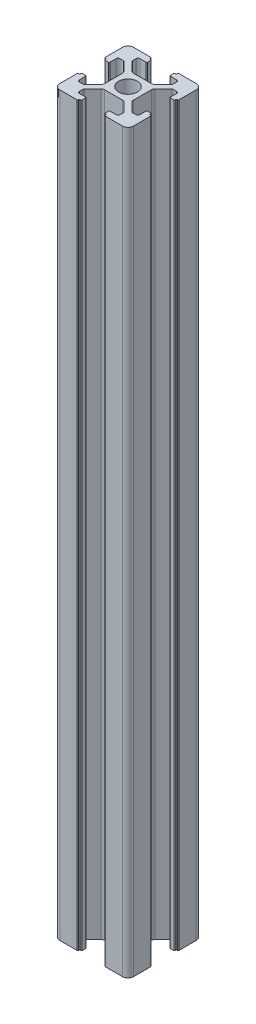
SolidWorks part; units mm, degrees
ref_plane "Front Plane" through (0, 0, 0) normal (0, 0, 1) x (1, 0, 0)
ref_plane "Top Plane" through (0, 0, 0) normal (0, 1, 0) x (1, 0, 0)
ref_plane "Right Plane" through (0, 0, 0) normal (1, 0, 0) x (0, 0, -1)
sketch "草图1" plane through (0, 0, 0) normal (0, 1, 0) x (1, 0, 0)
  line L5 (19.7612, 22.5335) -> (19.7612, 21.6335)
  line L8 (19.0112, 23.2335) -> (14.3612, 23.2335)
  line L9 (19.5612, 21.4335) -> (17.8612, 21.4335)
  line L10 (18.9612, 13.2335) -> (18.9612, 15.6586)
  line L11 (20.4361, 17.1335) -> (25.2863, 17.1335)
  line L12 (26.7612, 15.6586) -> (26.7612, 10.8084)
  line L13 (25.2863, 9.3335) -> (20.4361, 9.3335)
  line L14 (18.9612, 10.8084) -> (18.9612, 13.2335)
  line L15 (32.1612, 16.3335) -> (31.2612, 16.3335)
  line L16 (32.8612, 17.0835) -> (32.8612, 21.7335)
  line L17 (31.0612, 16.5335) -> (31.0612, 18.2335)
  line L18 (31.3612, 23.2335) -> (26.7112, 23.2335)
  line L19 (25.9612, 21.6335) -> (25.9612, 22.5335)
  line L20 (26.1612, 21.4335) -> (27.8612, 21.4335)
  line L21 (30.5612, 18.7335) -> (29.629, 18.7335)
  line L22 (32.6612, 16.8835) -> (32.5612, 16.8835)
  line L23 (28.3612, 20.0013) -> (28.3612, 20.9335)
  line L24 (27.0541, 16.3657) -> (29.2754, 18.5871)
  line L25 (25.9934, 17.4264) -> (28.2148, 19.6477)
  line L26 (32.3612, 16.6835) -> (32.3612, 16.5335)
  line L27 (26.5112, 23.0335) -> (26.5112, 22.9335)
  line L28 (12.8612, 21.7335) -> (12.8612, 17.0835)
  line L29 (26.3112, 22.7335) -> (26.1612, 22.7335)
  line L30 (14.4612, 16.3335) -> (13.5612, 16.3335)
  line L31 (25.9612, 3.9335) -> (25.9612, 4.8335)
  line L32 (26.7112, 3.2335) -> (31.3612, 3.2335)
  line L33 (14.6612, 16.5335) -> (14.6612, 18.2335)
  line L34 (17.3612, 20.9335) -> (17.3612, 20.0013)
  line L36 (19.2112, 23.0335) -> (19.2112, 22.9335)
  line L37 (16.0934, 18.7335) -> (15.1612, 18.7335)
  line L38 (19.729, 17.4264) -> (17.5077, 19.6477)
  line L39 (18.6683, 16.3657) -> (16.447, 18.5871)
  line L40 (19.4112, 22.7335) -> (19.5612, 22.7335)
  line L42 (13.0612, 16.8835) -> (13.1612, 16.8835)
  line L43 (13.3612, 16.6835) -> (13.3612, 16.5335)
  line L44 (26.1612, 5.0335) -> (27.8612, 5.0335)
  line L45 (32.8612, 4.7335) -> (32.8612, 9.3835)
  line L46 (31.2612, 10.1335) -> (32.1612, 10.1335)
  line L47 (31.0612, 9.9335) -> (31.0612, 8.2335)
  line L48 (28.3612, 5.5335) -> (28.3612, 6.4657)
  line L49 (26.5112, 3.4335) -> (26.5112, 3.5335)
  line L50 (29.629, 7.7335) -> (30.5612, 7.7335)
  line L51 (25.9934, 9.0406) -> (28.2148, 6.8193)
  line L52 (27.0541, 10.1013) -> (29.2754, 7.8799)
  line L53 (26.3112, 3.7335) -> (26.1612, 3.7335)
  line L54 (32.6612, 9.5835) -> (32.5612, 9.5835)
  line L55 (32.3612, 9.7835) -> (32.3612, 9.9335)
  line L56 (13.5612, 10.1335) -> (14.4612, 10.1335)
  line L57 (12.8612, 9.3835) -> (12.8612, 4.7335)
  line L58 (14.6612, 9.9335) -> (14.6612, 8.2335)
  line L59 (14.3612, 3.2335) -> (19.0112, 3.2335)
  line L60 (19.7612, 4.8335) -> (19.7612, 3.9335)
  line L61 (19.5612, 5.0335) -> (17.8612, 5.0335)
  line L62 (15.1612, 7.7335) -> (16.0934, 7.7335)
  line L63 (13.0612, 9.5835) -> (13.1612, 9.5835)
  line L64 (17.3612, 6.4657) -> (17.3612, 5.5335)
  line L65 (18.6683, 10.1013) -> (16.447, 7.8799)
  line L66 (19.729, 9.0406) -> (17.5077, 6.8193)
  line L67 (13.3612, 9.7835) -> (13.3612, 9.9335)
  line L68 (19.2112, 3.4335) -> (19.2112, 3.5335)
  line L69 (19.4112, 3.7335) -> (19.5612, 3.7335)
  circle A0 centre (22.8612, 13.2335) radius 2.55
  arc A1 (14.3612, 23.2335) -> (12.8612, 21.7335) centre (14.3612, 21.7335) ccw
  arc A2 (32.8612, 21.7335) -> (31.3612, 23.2335) centre (31.3612, 21.7335) ccw
  arc A3 (31.3612, 3.2335) -> (32.8612, 4.7335) centre (31.3612, 4.7335) ccw
  arc A4 (12.8612, 4.7335) -> (14.3612, 3.2335) centre (14.3612, 4.7335) ccw
  arc A5 (14.6612, 8.2335) -> (15.1612, 7.7335) centre (15.1612, 8.2335) ccw
  arc A6 (17.8612, 5.0335) -> (17.3612, 5.5335) centre (17.8612, 5.5335) cw
  arc A7 (27.8612, 5.0335) -> (28.3612, 5.5335) centre (27.8612, 5.5335) ccw
  arc A8 (31.0612, 8.2335) -> (30.5612, 7.7335) centre (30.5612, 8.2335) cw
  arc A9 (31.0612, 18.2335) -> (30.5612, 18.7335) centre (30.5612, 18.2335) ccw
  arc A10 (27.8612, 21.4335) -> (28.3612, 20.9335) centre (27.8612, 20.9335) cw
  arc A11 (17.8612, 21.4335) -> (17.3612, 20.9335) centre (17.8612, 20.9335) ccw
  arc A12 (14.6612, 18.2335) -> (15.1612, 18.7335) centre (15.1612, 18.2335) cw
  arc A13 (16.0934, 7.7335) -> (16.447, 7.8799) centre (16.0934, 8.2335) ccw
  arc A14 (17.3612, 6.4657) -> (17.5077, 6.8193) centre (17.8612, 6.4657) cw
  arc A15 (28.3612, 6.4657) -> (28.2148, 6.8193) centre (27.8612, 6.4657) ccw
  arc A16 (29.629, 7.7335) -> (29.2754, 7.8799) centre (29.629, 8.2335) cw
  arc A17 (29.629, 18.7335) -> (29.2754, 18.5871) centre (29.629, 18.2335) ccw
  arc A18 (28.3612, 20.0013) -> (28.2148, 19.6477) centre (27.8612, 20.0013) cw
  arc A19 (17.5077, 19.6477) -> (17.3612, 20.0013) centre (17.8612, 20.0013) cw
  arc A20 (16.447, 18.5871) -> (16.0934, 18.7335) centre (16.0934, 18.2335) ccw
  arc A21 (14.4612, 10.1335) -> (14.6612, 9.9335) centre (14.4612, 9.9335) cw
  arc A22 (13.5612, 10.1335) -> (13.3612, 9.9335) centre (13.5612, 9.9335) ccw
  arc A23 (13.1612, 9.5835) -> (13.3612, 9.7835) centre (13.1612, 9.7835) ccw
  arc A24 (12.8612, 9.3835) -> (13.0612, 9.5835) centre (13.0612, 9.3835) cw
  arc A25 (19.0112, 3.2335) -> (19.2112, 3.4335) centre (19.0112, 3.4335) ccw
  arc A26 (19.2112, 3.5335) -> (19.4112, 3.7335) centre (19.4112, 3.5335) cw
  arc A27 (19.7612, 3.9335) -> (19.5612, 3.7335) centre (19.5612, 3.9335) cw
  arc A28 (19.7612, 4.8335) -> (19.5612, 5.0335) centre (19.5612, 4.8335) ccw
  arc A29 (26.7112, 3.2335) -> (26.5112, 3.4335) centre (26.7112, 3.4335) cw
  arc A30 (26.5112, 3.5335) -> (26.3112, 3.7335) centre (26.3112, 3.5335) ccw
  arc A31 (25.9612, 3.9335) -> (26.1612, 3.7335) centre (26.1612, 3.9335) ccw
  arc A32 (25.9612, 4.8335) -> (26.1612, 5.0335) centre (26.1612, 4.8335) cw
  arc A33 (32.8612, 9.3835) -> (32.6612, 9.5835) centre (32.6612, 9.3835) ccw
  arc A34 (32.5612, 9.5835) -> (32.3612, 9.7835) centre (32.5612, 9.7835) cw
  arc A35 (32.1612, 10.1335) -> (32.3612, 9.9335) centre (32.1612, 9.9335) cw
  arc A36 (31.2612, 10.1335) -> (31.0612, 9.9335) centre (31.2612, 9.9335) ccw
  arc A37 (32.8612, 17.0835) -> (32.6612, 16.8835) centre (32.6612, 17.0835) cw
  arc A38 (32.5612, 16.8835) -> (32.3612, 16.6835) centre (32.5612, 16.6835) ccw
  arc A39 (32.1612, 16.3335) -> (32.3612, 16.5335) centre (32.1612, 16.5335) ccw
  arc A40 (31.2612, 16.3335) -> (31.0612, 16.5335) centre (31.2612, 16.5335) cw
  arc A41 (25.9612, 21.6335) -> (26.1612, 21.4335) centre (26.1612, 21.6335) ccw
  arc A42 (25.9612, 22.5335) -> (26.1612, 22.7335) centre (26.1612, 22.5335) cw
  arc A43 (26.5112, 22.9335) -> (26.3112, 22.7335) centre (26.3112, 22.9335) cw
  arc A44 (26.7112, 23.2335) -> (26.5112, 23.0335) centre (26.7112, 23.0335) ccw
  arc A45 (14.4612, 16.3335) -> (14.6612, 16.5335) centre (14.4612, 16.5335) ccw
  arc A46 (19.7612, 21.6335) -> (19.5612, 21.4335) centre (19.5612, 21.6335) cw
  arc A47 (19.5612, 22.7335) -> (19.7612, 22.5335) centre (19.5612, 22.5335) cw
  arc A48 (19.2112, 22.9335) -> (19.4112, 22.7335) centre (19.4112, 22.9335) ccw
  arc A49 (19.0112, 23.2335) -> (19.2112, 23.0335) centre (19.0112, 23.0335) cw
  arc A50 (13.3612, 16.5335) -> (13.5612, 16.3335) centre (13.5612, 16.5335) ccw
  arc A51 (13.1612, 16.8835) -> (13.3612, 16.6835) centre (13.1612, 16.6835) cw
  arc A52 (12.8612, 17.0835) -> (13.0612, 16.8835) centre (13.0612, 17.0835) ccw
  arc A53 (18.9612, 10.8084) -> (18.6683, 10.1013) centre (17.9612, 10.8084) cw
  arc A54 (19.729, 9.0406) -> (20.4361, 9.3335) centre (20.4361, 8.3335) cw
  arc A55 (25.9934, 9.0406) -> (25.2863, 9.3335) centre (25.2863, 8.3335) ccw
  arc A56 (27.0541, 10.1013) -> (26.7612, 10.8084) centre (27.7612, 10.8084) cw
  arc A57 (27.0541, 16.3657) -> (26.7612, 15.6586) centre (27.7612, 15.6586) ccw
  arc A58 (25.9934, 17.4264) -> (25.2863, 17.1335) centre (25.2863, 18.1335) cw
  arc A59 (20.4361, 17.1335) -> (19.729, 17.4264) centre (20.4361, 18.1335) cw
  arc A60 (18.9612, 15.6586) -> (18.6683, 16.3657) centre (17.9612, 15.6586) ccw
  dimension "D1" = 4
  dimension "D2" = 1.5
  dimension "D3" = 0.5
  dimension "D4" = 0.5
  dimension "D5" = 0.2
  dimension "D6" = 1
extrude "凸台-拉伸1" add sketch "草图1" along normal blind 200
